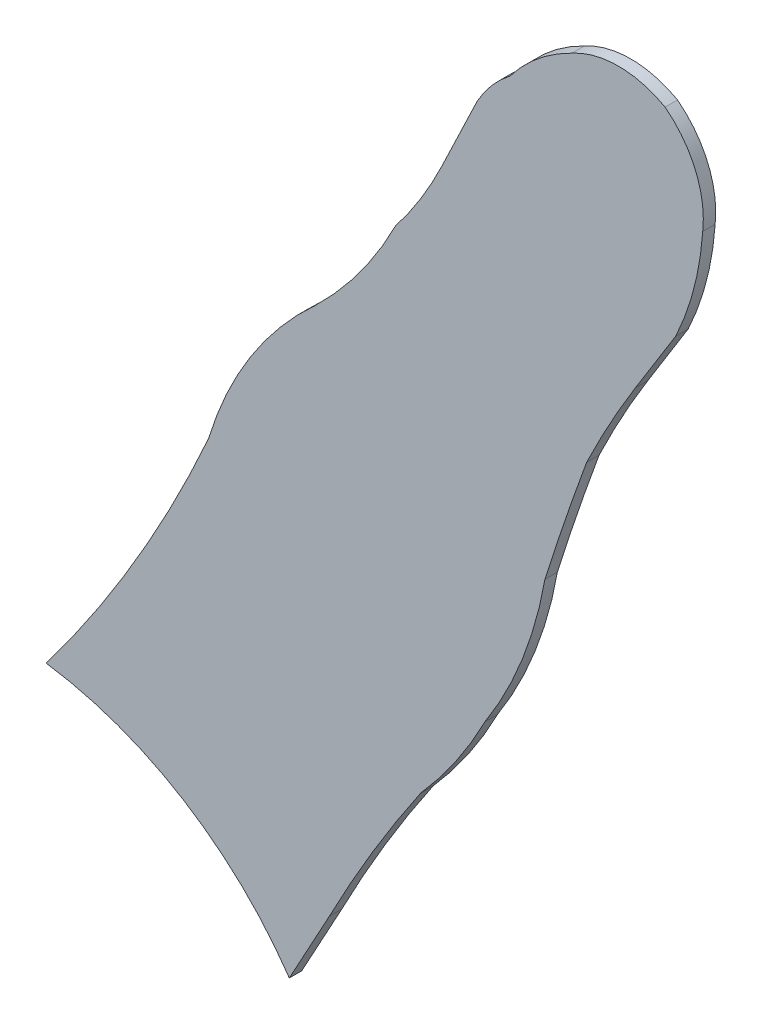
SolidWorks part; units mm, degrees
ref_plane "Front Plane" through (0, 0, 0) normal (0, 0, 1) x (1, 0, 0)
ref_plane "Top Plane" through (0, 0, 0) normal (0, 1, 0) x (1, 0, 0)
ref_plane "Right Plane" through (0, 0, 0) normal (1, 0, 0) x (0, 0, -1)
sketch "Sketch1" plane through (0, 0, 0) normal (0, 0, 1) x (1, 0, 0)
  line L0 (612.6848, 638.6806) -> (1092.6848, 638.6806) construction
  line L1 (61.7197, 1004.0401) -> (90.1216, 1063.4435)
  line L2 (217.5571, 927.4546) -> (249.9932, 979.6393)
  line L4 (-61.0803, 376.6667) -> (-28.8433, 435.8107)
  arc A0 (-256.7347, 498.2784) -> (-126.0153, 720.3858) centre (-1159.6791, 1179.2194) ccw
  arc A1 (-40.4114, 855.7325) -> (24.3699, 943.65) centre (-268.6333, 1091.7215) ccw
  arc A2 (-126.0153, 720.3858) -> (-40.4114, 855.7325) centre (160.3893, 633.9857) cw
  arc A3 (24.3699, 943.65) -> (61.7197, 1004.0401) centre (-235.706, 1146.2451) ccw
  arc A4 (-28.8433, 435.8107) -> (44.6754, 558.4325) centre (1024.9395, -112.6419) cw
  arc A5 (44.6754, 558.4325) -> (96.398, 633.9857) centre (-231.1751, 802.7566) ccw
  arc A6 (96.398, 633.9857) -> (144.6781, 757.4037) centre (-184.5531, 815.0437) ccw
  arc A7 (144.6781, 757.4037) -> (178.2255, 855.7325) centre (2226.3563, 102.0712) cw
  arc A8 (178.2255, 855.7325) -> (217.5571, 927.4546) centre (854.993, 531.2475) cw
  arc A9 (90.1216, 1063.4435) -> (116.6855, 1094.3968) centre (177.6005, 1015.2447) cw
  arc A10 (249.9932, 979.6393) -> (271.7178, 1063.4435) centre (37.1929, 1079.5216) ccw
  arc A11 (271.7178, 1063.4435) -> (241.455, 1135.0651) centre (192.6729, 1072.2485) ccw
  arc A12 (241.455, 1135.0651) -> (166.2448, 1135.0651) centre (203.8499, 1068.0092) ccw
  arc A13 (166.2448, 1135.0651) -> (116.6855, 1094.3968) centre (226.0311, 1011.677) ccw
  arc A14 (-256.7347, 498.2784) -> (-61.0803, 376.6667) centre (-296.9077, 215.4516) cw
  dimension "D1" = 1130.924
  dimension "D2" = 328.2927
  dimension "D3" = 299.153
  dimension "D4" = 329.673
  dimension "D5" = 1187.964
  dimension "D6" = 368.4939
  dimension "D7" = 334.2388
  dimension "D8" = 2182.3943
  dimension "D9" = 750.5362
  dimension "D10" = 99.8783
  dimension "D11" = 235.0754
  dimension "D12" = 79.5338
  dimension "D13" = 76.8807
  dimension "D14" = 137.1095
  dimension "D15" = 24.3699
  dimension "D16" = 37.1929
  dimension "D17" = 44.6754
  dimension "D18" = 61.7197
  dimension "D19" = 90.1216
  dimension "D20" = 96.398
  dimension "D21" = 116.6855
  dimension "D22" = 144.6781
  dimension "D23" = 160.3893
  dimension "D24" = 166.2448
  dimension "D25" = 177.6005
  dimension "D26" = 178.2255
  dimension "D27" = 192.6729
  dimension "D28" = 203.8499
  dimension "D29" = 217.5571
  dimension "D30" = 226.0311
  dimension "D31" = 249.9932
  dimension "D32" = 854.993
  dimension "D33" = 2226.3563
  dimension "D34" = 40.4114
  dimension "D35" = 1024.9395
  dimension "D36" = 235.706
  dimension "D37" = 28.8433
  dimension "D38" = 102.0712
  dimension "D39" = 61.0803
  dimension "D40" = 126.0153
  dimension "D42" = 231.1751
  dimension "D44" = 256.7347
  dimension "D46" = 1159.6791
  dimension "D50" = 638.6806
extrude "Boss-Extrude3" add sketch "Sketch1" along normal blind 10
sketch "Sketch2" plane through (0, 0, 10) normal (0, 0, 1) x (1, 0, 0)
  arc A0 (-256.7347, 498.2784) -> (-61.0803, 376.6667) centre (-296.9077, 215.4516) cw
  dimension "D1" = 285.6656
